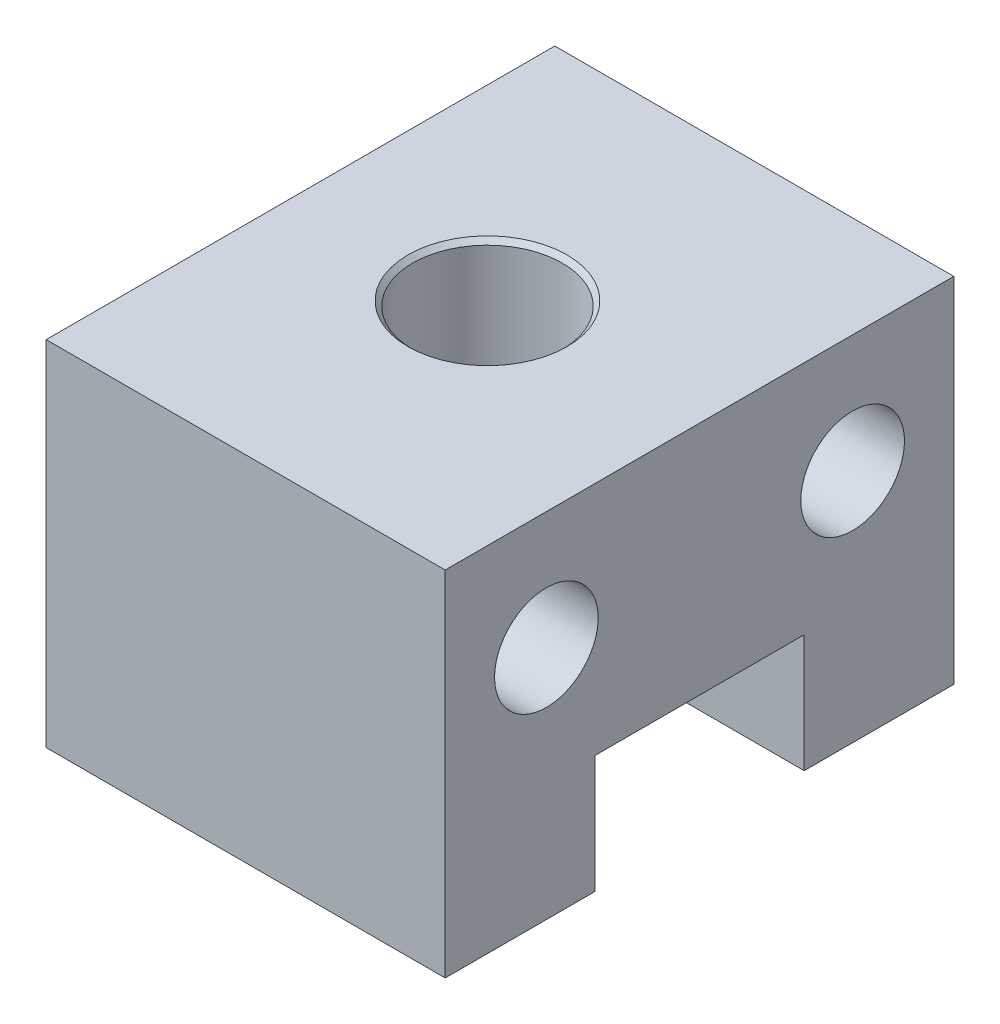
SolidWorks part; units mm, degrees
material "Plain Carbon Steel"
ref_plane "Front Plane" through (0, 0, 0) normal (0, 0, 1) x (1, 0, 0)
ref_plane "Top Plane" through (0, 0, 0) normal (0, 1, 0) x (1, 0, 0)
ref_plane "Right Plane" through (0, 0, 0) normal (1, 0, 0) x (0, 0, -1)
sketch "Sketch1" plane through (0, 0, 0) normal (0, 1, 0) x (1, 0, 0)
  line L1 (-44.45, 53.975) -> (44.45, 53.975)
  line L2 (-44.45, 53.975) -> (-44.45, -53.975)
  line L3 (-44.45, -53.975) -> (44.45, -53.975)
  line L4 (44.45, 53.975) -> (44.45, -53.975)
  line L5 (-44.45, 53.975) -> (44.45, -53.975) construction
  line L6 (-44.45, -53.975) -> (44.45, 53.975) construction
  point P0 (0, 0)
  dimension "D1" = 107.95
  dimension "D2" = 88.9
extrude "Extrude1" add sketch "Sketch1" along normal blind 75
sketch "Sketch2" plane through (0, 75, 0) normal (0, 1, 0) x (1, 0, 0)
  line L0 (44.45, -53.975) -> (44.45, 53.975) construction
  line L1 (0, 0) -> (-4.7625, 0) construction
  circle A0 centre (-4.7625, 0) radius 14.2875
  point P2 (44.45, 0)
  dimension "D2" = 28.575
  dimension "D1" = 49.2125
extrude "Extrude2" cut sketch "Sketch2" against normal blind 203.2
hole_wizard "M6 Tapped Hole1" positions "Sketch4" profile "Sketch3" tap size "M6" standard "Peddi DIN"
sketch "Sketch4" plane through (0, 0, 0) normal (0, -1, 0) x (1, 0, 0)
  line L1 (13.3985, 34.925) -> (-22.9235, 34.925) construction
  line L2 (13.3985, 34.925) -> (13.3985, -34.925) construction
  line L3 (13.3985, -34.925) -> (-22.9235, -34.925) construction
  line L4 (-22.9235, 34.925) -> (-22.9235, -34.925) construction
  line L5 (-22.9235, 0) -> (13.3985, 0) construction
  line L9 (-4.7625, -34.925) -> (-4.7625, 0) construction
  point P0 (-22.9235, 34.925)
  point P1 (13.3985, 34.925)
  point P3 (-22.9235, -34.925)
  point P5 (13.3985, -34.925)
  dimension "D1" = 36.322
  dimension "D2" = 69.85
sketch "Sketch3" plane through (-22.9235, 0, 34.925) normal (1, 0, 0) x (0, 0, -1)
  line L0 (0, 0) -> (0, 29.493)
  line L1 (0, 29.493) -> (2.5, 27.9908)
  line L2 (2.5, 27.9908) -> (2.5, 0)
  line L5 (2.5, 0) -> (0, 0)
  line L10 (0, 29.493) -> (-2.5, 27.9908) construction
  line L11 (0, -6.35) -> (0, 107.95) construction
  dimension "Tap Drill Dia." = 5
  dimension "Tap Drill Depth" = 27.9908
  dimension "Drill Angle" = 118
cosmetic thread "Hole Thread1" parameters "D1"=15.0114, "D2"=6
cosmetic thread "Hole Thread2" parameters "D1"=15.0114, "D2"=6
cosmetic thread "Hole Thread3" parameters "D1"=15.0114, "D2"=6
cosmetic thread "Hole Thread4" parameters "D1"=15.0114, "D2"=6
sketch "Sketch6" plane through (0, 75, 0) normal (0, 1, 0) x (1, 0, 0)
  circle A0 centre (-4.7625, 0) radius 15.875
  dimension "D1" = 31.75
extrude "Extrude4" cut sketch "Sketch6" against normal blind 38.354
sketch "Sketch7" plane through (0, 0, 0) normal (0, -1, 0) x (1, 0, 0)
  line L0 (44.45, 53.975) -> (44.45, -53.975) construction
  line L1 (44.45, 22.225) -> (-44.45, 22.225)
  line L2 (44.45, 22.225) -> (44.45, -22.225)
  line L3 (44.45, -22.225) -> (-44.45, -22.225)
  line L4 (-44.45, 22.225) -> (-44.45, -22.225)
  line L5 (-44.45, -53.975) -> (-44.45, 53.975) construction
  line L6 (0, 0) -> (44.45, 0) construction
  dimension "D2" = 44.45
extrude "Extrude5" cut sketch "Sketch7" against normal blind 25
sketch "Sketch8" plane through (0, 75, 0) normal (0, 1, 0) x (1, 0, 0)
  line L0 (-44.45, -53.975) -> (44.45, -53.975) construction
  line L1 (44.45, 53.975) -> (40.2375, 53.975)
  line L2 (44.45, 53.975) -> (44.45, -53.975)
  line L3 (44.45, -53.975) -> (40.2375, -53.975)
  line L4 (40.2375, 53.975) -> (40.2375, -53.975)
  circle A0 centre (-4.7625, 0) radius 15.875 construction
  dimension "D1" = 45
extrude "Extrude6" cut sketch "Sketch8" against normal through all
hole_wizard "CBORE for M20 SHCS1" positions "Sketch10" profile "Sketch9" counterbore size "M20" standard "Ansi Metric" end condition through all
sketch "Sketch10" plane through (-44.45, 0, 0) normal (-1, 0, 0) x (0, 0, 1)
  line L0 (32.5, 50) -> (-32.5, 50) construction
  line L3 (0, 0) -> (0, 50) construction
  line L8 (22.225, 0) -> (53.975, 0) construction
  point P0 (32.5, 50)
  point P1 (-32.5, 50)
  dimension "D1" = 65
  dimension "D2" = 50
sketch "Sketch9" plane through (-44.45, 50, 32.5) normal (0, 1, 0) x (0, 0, 1)
  line L0 (0, 0) -> (0, 84.6875)
  line L1 (0, 84.6875) -> (11, 84.6875)
  line L3 (11, 84.6875) -> (11, 20)
  line L4 (11, 20) -> (16.5, 20)
  line L5 (16.5, 20) -> (16.5, 0)
  line L7 (16.5, 0) -> (0, 0)
  line L11 (0, -6.35) -> (0, 107.95) construction
  dimension "Thru Hole Dia." = 22
  dimension "Thru Hole Depth" = 84.6875
  dimension "C'Bore Dia." = 33
  dimension "C'Bore Depth" = 20
chamfer "Chamfer1" distance 1 angle 45 1 edges at (-4.7625, 75, 15.875)
